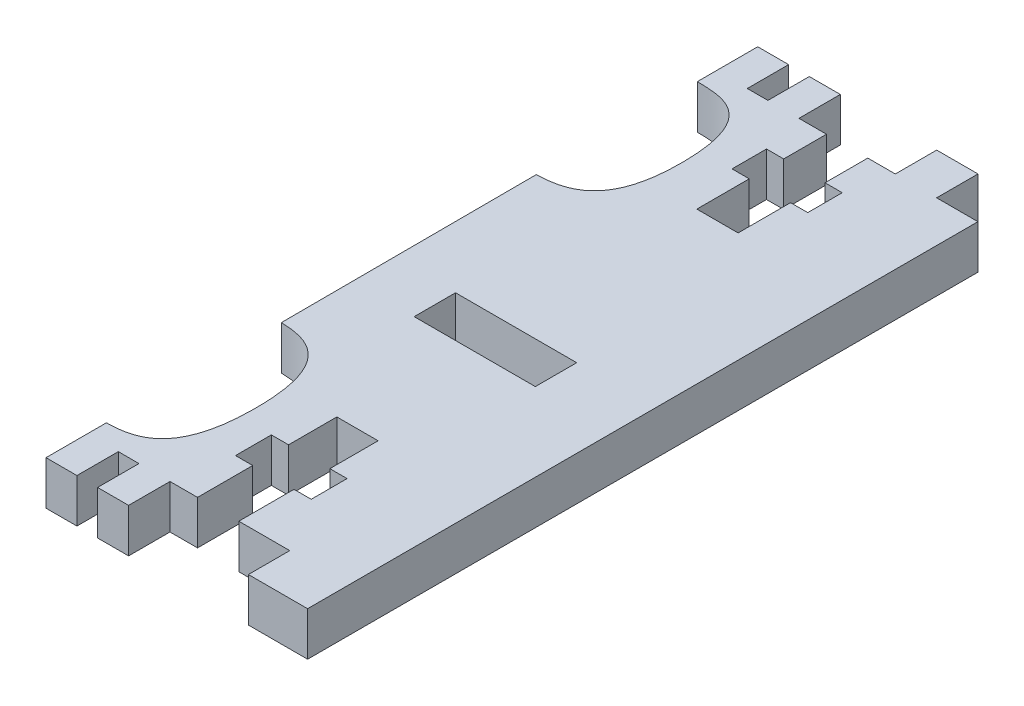
SolidWorks part; units mm, degrees
ref_plane "Front Plane" through (0, 0, 0) normal (0, 0, 1) x (1, 0, 0)
ref_plane "Top Plane" through (0, 0, 0) normal (0, 1, 0) x (1, 0, 0)
ref_plane "Right Plane" through (0, 0, 0) normal (1, 0, 0) x (0, 0, -1)
sketch "Sketch1" plane through (0, 0, 0) normal (0, 1, 0) x (1, 0, 0)
  line L0 (-9.4831, -21.4709) -> (-9.4831, -25.851)
  line L1 (-9.4831, 21.3709) -> (-9.4831, 25.751)
  line L2 (-9.4831, 25.751) -> (-7.2402, 25.751)
  line L3 (6.4884, 25.751) -> (6.4884, 22.7509)
  line L4 (6.4884, 22.7509) -> (9.4831, 22.7509)
  line L5 (9.4831, 22.7509) -> (9.4831, -25.851)
  line L6 (-9.4831, -25.851) -> (-7.2402, -25.851)
  line L7 (-4.9911, -0.65) -> (-4.9911, -3.6501)
  line L8 (-4.9911, -3.6501) -> (3.7933, -3.6501)
  line L9 (3.7933, -3.6501) -> (3.7933, -0.65)
  line L10 (3.7933, -0.65) -> (-4.9911, -0.65)
  line L11 (-3.4938, -25.851) -> (-3.4938, -22.8508)
  line L12 (-3.4938, -22.8508) -> (-1.4973, -22.8508)
  line L13 (-1.4973, -22.8508) -> (-1.4973, -18.8507)
  line L14 (-1.4973, -18.8507) -> (-2.745, -18.8507)
  line L15 (-2.745, -18.8507) -> (-2.745, -18.7507)
  line L16 (-2.745, -18.7507) -> (-2.745, -16.2506)
  line L17 (-2.745, -16.2506) -> (-1.4973, -16.2506)
  line L18 (-1.4973, -16.2506) -> (-1.4973, -12.7504)
  line L19 (-1.4973, -12.7504) -> (1.4972, -12.7504)
  line L20 (1.4972, -12.7504) -> (1.4972, -16.2506)
  line L21 (1.4972, -16.2506) -> (2.745, -16.2506)
  line L22 (2.745, -16.2506) -> (2.745, -18.7507)
  line L23 (2.745, -18.7507) -> (2.745, -18.8507)
  line L24 (2.745, -18.8507) -> (1.4972, -18.8507)
  line L25 (1.4972, -18.8507) -> (1.4972, -22.8508)
  line L26 (1.4972, -22.8508) -> (5.1908, -22.8508)
  line L27 (5.1908, -22.8508) -> (5.1908, -25.851)
  line L28 (3.4937, 25.751) -> (3.4937, 22.7509)
  line L29 (3.4937, 22.7509) -> (1.4972, 22.7509)
  line L30 (1.4972, 22.7509) -> (1.4972, 19.6507)
  line L31 (1.4972, 19.6507) -> (2.745, 19.6507)
  line L32 (2.745, 19.6507) -> (2.745, 17.1507)
  line L33 (2.745, 17.1507) -> (1.4972, 17.1507)
  line L34 (1.4972, 17.1507) -> (1.4972, 13.3504)
  line L35 (1.4972, 13.3504) -> (-1.4973, 13.3504)
  line L36 (-1.4973, 13.3504) -> (-1.4973, 17.1507)
  line L37 (-1.4973, 17.1507) -> (-2.745, 17.1507)
  line L38 (-2.745, 17.1507) -> (-2.745, 19.6507)
  line L39 (-2.745, 19.6507) -> (-1.4973, 19.6507)
  line L40 (-1.4973, 19.6507) -> (-1.4973, 22.7509)
  line L41 (-1.4973, 22.7509) -> (-3.4938, 22.7509)
  line L42 (-3.4938, 22.7509) -> (-3.4938, 25.751)
  line L43 (-7.2402, 25.751) -> (-7.3857, 25.8302)
  line L44 (-5.7428, 25.751) -> (-5.7428, 22.7509)
  line L45 (-5.7428, 22.7509) -> (-7.2402, 22.7509)
  line L46 (-7.2402, 22.7509) -> (-7.2402, 25.751)
  line L47 (-7.2402, -22.8508) -> (-5.7428, -22.8508)
  line L48 (-5.7428, -22.8508) -> (-5.7428, -25.851)
  line L49 (-5.7428, -25.851) -> (-3.4938, -25.851)
  line L50 (-7.2402, -25.851) -> (-7.2402, -22.8508)
  line L51 (-5.7428, 25.751) -> (-3.4938, 25.751)
  line L52 (-3.4938, 25.751) -> (-3.5802, 25.8302)
  line L53 (3.4937, 25.751) -> (6.4884, 25.751)
  line L54 (-9.4831, 9.693) -> (-9.4312, -8.8341)
  line L55 (5.1908, -25.851) -> (9.4831, -25.851)
  spline S1 degree 3 poles (-9.4312, -8.8341) (-7.1882, -8.8985) (-4.9654, -9.6433) (-4.9951, -15.2629) knots 1 1 1 1 2 2 2 2
  spline S2 degree 3 poles (-4.9951, -15.2629) (-5.0248, -20.8823) (-7.4265, -21.4438) (-9.4831, -21.4709) knots 2 2 2 2 3 3 3 3
  spline S4 degree 3 poles (-9.4831, 9.693) (-7.2402, 9.7574) (-4.8898, 10.4982) (-4.9525, 15.8863) knots 5 5 5 5 6 6 6 6
  spline S5 degree 3 poles (-4.9525, 15.8863) (-5.0152, 21.2742) (-7.4265, 21.3438) (-9.4831, 21.3709) knots 6 6 6 6 7 7 7 7
extrude "Boss-Extrude1" add sketch "Sketch1" along normal blind 3.175 contours S5 S4 L54 S1 S2 L0 L6 L50 L47 L48 L49 L11 L12 L13 L14 L15 L16 L17 L18 L19 L20 L21 L22 L23 L24 L25 L26 L27 L55 L5 L4 L3 L53 L28 L29 L30 L31 L32 L33 L34 L35 L36 L37 L38 L39 L40 L41 L42 L51 L44 L45
